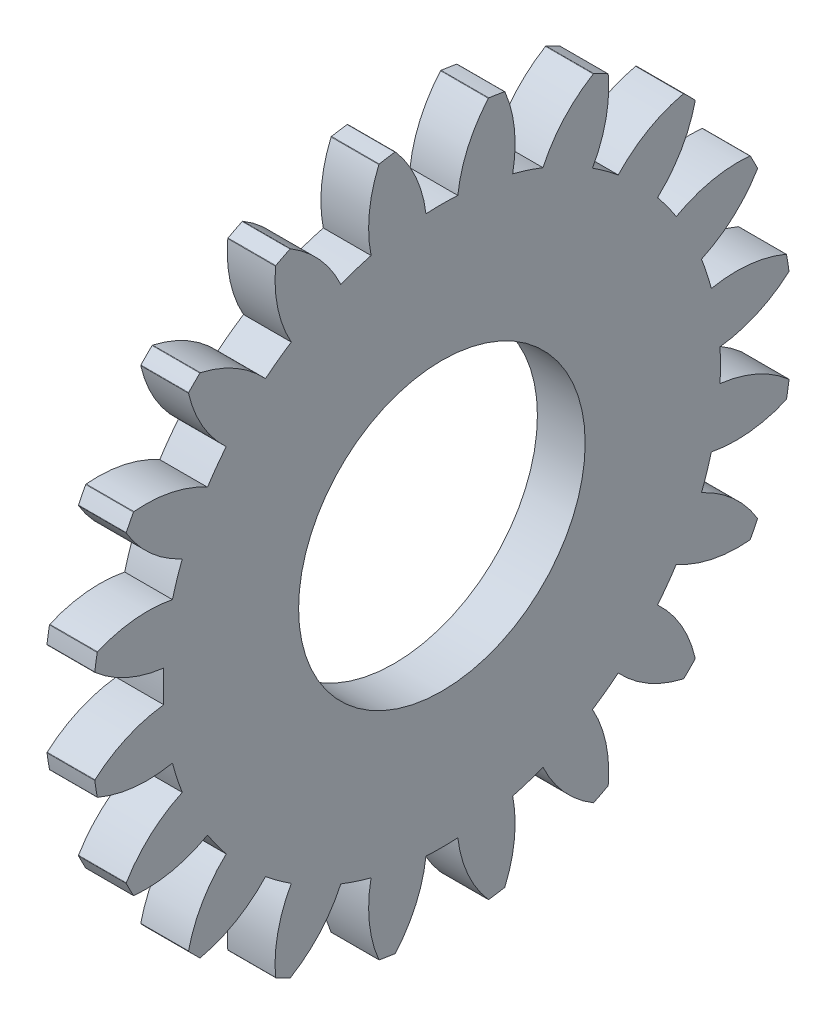
SolidWorks part; units mm, degrees
material "Zinc AC41A Alloy, As Cast"
ref_plane "Plane1" through (0, 0, 0) normal (0, 0, 1) x (1, 0, 0)
ref_plane "Plane2" through (0, 0, 0) normal (0, 1, 0) x (1, 0, 0)
ref_plane "Plane3" through (0, 0, 0) normal (1, 0, 0) x (0, 0, -1)
sketch "HoldingSke" plane through (0, 0, 0) normal (0, 1, 0) x (1, 0, 0)
  line L0 (0, 0) -> (0.9397, -0.342)
  line L1 (-15, 0) -> (100, 0) construction
  line L2 (0, 0) -> (-2.1039, 2.3779)
  line L3 (0, 0) -> (-11.863, 4.5341)
  line L4 (0, 0) -> (8.1152, 2.9537)
  line L5 (0, 0) -> (-46.8476, -17.4728)
  line L6 (0, 0) -> (-1.2434, -0.839)
  line L7 (-2.1039, 2.3779) -> (8.6586, 51.2059)
  line L8 (-76.2, 54.61) -> (-74.8, 54.61)
  line L9 (-71.009, 38.7566) -> (-53.1078, 45.2721)
  line L10 (-76.2, 71.12) -> (104.1128, 71.12)
  line L11 (0, 0) -> (-1.5, 0)
  line L12 (-76.2, 101.6) -> (-76.162, 101.6)
  line L13 (24.9733, 27.94) -> (52.9518, 28.4284)
  line L14 (24.9733, 27.94) -> (24.9743, 27.94)
  line L15 (24.9733, 27.94) -> (100.4006, 29.5858)
  line L16 (-63.627, -1) -> (-12.827, -1)
  circle A0 centre (0, 0) radius 4.5
  circle A1 centre (0, 0) radius 8.749
  circle A2 centre (0, 0) radius 37.5
  circle A3 centre (0, 0) radius 4.5
  dimension "MHD" = 17.498
  dimension "Hub_dia" = 75
  dimension "Bore" = 9
  dimension "MBD" = 9
  dimension "Num_teeth" = 20
  dimension "Pitch" = 1
  dimension "Overall_len" = 50
  dimension "Show_teeth" = 20
  dimension "Thickness" = 1.5
  dimension "OAL" = 50.0001
  dimension "T_dim" = 1.4
  dimension "Ap" = 20
  dimension "H" = 19.05
  dimension "Pitch_radius" = 180.3128
  dimension "Width" = 1.5
  dimension "Backlash" = 0.038
  dimension "Addendum_fac" = 1
  dimension "Dedendum_fac" = 1.25
  dimension "Clearance_fac" = 0.25
  dimension "Dedendum_add" = 0.001
  dimension "Module" = 1
sketch "BasProSke" plane through (0, 0, 0) normal (0, 1, 0) x (1, 0, 0)
  line L0 (-10, 0) -> (60, 0) construction
  line L1 (0, 0) -> (0, 11)
  line L2 (0, 0) -> (1.5, 0)
  line L3 (1.5, 0) -> (1.5, 11)
  line L4 (1.5, 11) -> (0, 11)
  dimension "Thickness" = 1.5
  dimension "Diameter" = 22
revolve "Base-Revolve" add sketch "BasProSke" angle 360 about L0
sketch "TooCutSke" plane through (0, 0, 0) normal (1, 0, 0) x (0, 0, -1)
  line L1 (0, 0) -> (0, 107) construction
  line L2 (0, 0) -> (-0.8511, 9.9637) construction
  line L3 (0, 0) -> (-3.1206, 19.7028) construction
  line L4 (-0.8511, 9.9637) -> (-1.5603, 9.8514) construction
  arc A0 (0.4999, 8.7347) -> (-0.4999, 8.7347) centre (0, 0) ccw
  arc A1 (1.4852, 10.9249) -> (-1.4852, 10.9249) centre (0, 0) ccw
  circle A2 centre (0, 0) radius 10 construction
  circle A3 centre (0, 0) radius 9.3969 construction
  arc A4 (-0.4999, 8.7347) -> (-1.4852, 10.9249) centre (-4.4722, 8.2645) ccw
  arc A5 (1.4852, 10.9249) -> (0.4999, 8.7347) centre (4.4722, 8.2645) ccw
  dimension "Root_dia" = 17.498
  dimension "Overcut_dia" = 22.0508
  dimension "Pitch_dia" = 20
  dimension "Base_dia" = 18.7939
  dimension "Flank_rad" = 4
  dimension "Half_ang" = 9
  dimension "Half_CT" = 0.7181
extrude "ToothCut" cut sketch "TooCutSke" along normal through all
fillet "Breaks" radius 0.02 2 edges at (0.75, 10.902, -1.465) (0.75, 10.902, 1.465)
fillet "RootFillets" [suppressed] radius 0.251
pattern_circular "TeethCuts" count 20 every 18 about axis through (-10, 0, 0) along (1, 0, 0) of "ToothCut", "RootFillets", "Breaks"
sketch "HubNeaOneSke" plane through (0, 0, 0) normal (-1, 0, 0) x (0, 0, 1)
  circle A0 centre (0, 0) radius 8.749
  dimension "Diameter" = 17.498
extrude "HubNearOne" [suppressed] add sketch "HubNeaOneSke" along normal blind 48.5001
sketch "HubNeaBotSke" plane through (0, 0, 0) normal (-1, 0, 0) x (0, 0, 1)
  circle A0 centre (0, 0) radius 8.749
  dimension "Diameter" = 17.498
extrude "HubNearBoth" [suppressed] add sketch "HubNeaBotSke" along normal blind 24.25
ref_plane "FarPln" through (1.5, 0, 0) normal (1, 0, 0) x (0, 0, -1)
sketch "HubFarSke" plane through (1.5, 0, 0) normal (1, 0, 0) x (0, 0, -1)
  circle A0 centre (0, 0) radius 8.749
  dimension "Diameter" = 17.498
extrude "HubFar" [suppressed] add sketch "HubFarSke" along normal blind 24.25
sketch "BorSke" plane through (0, 0, 0) normal (1, 0, 0) x (0, 0, -1)
  circle A0 centre (0, 0) radius 4.5
  dimension "Diameter" = 9
extrude "Bore" cut sketch "BorSke" along normal mid plane 100.0001
sketch "KeySke" plane through (0, 0, 0) normal (1, 0, 0) x (0, 0, -1)
  line L0 (-1.5, 0) -> (-1.5, 5.9)
  line L1 (-1.5, 5.9) -> (1.5, 5.9)
  line L2 (1.5, 5.9) -> (1.5, 0)
  line L3 (0, 0) -> (0, 34) construction
  line L4 (-1.5, 0) -> (1.5, 0)
  dimension "Offset" = 5.9
  dimension "Width" = 3
extrude "Keyway" [suppressed] cut sketch "KeySke" along normal mid plane 100.0001
pattern_circular "Keyway2" [suppressed] count 2 every 90 about axis through (-10, 0, 0) along (1, 0, 0)
equation "' \"Module@HoldingSke\" = 6.35"
equation "' \"Num_teeth@HoldingSke\" = 12"
equation "' \"Ap@HoldingSke\" =  20"
equation "' \"Ap@HoldingSke\" = 20"
equation "' \"Width@HoldingSke\" = 0.5 * 25.4"
equation "' \"Hub_dia@HoldingSke\"= 1 * 25.4"
equation "' \"Hub_dia@HoldingSke\" = 1 * 25.4"
equation "' \"Overall_len@HoldingSke\" = 1.0 * 25.4"
equation "' \"Bore@HoldingSke\" = 0.75 * 25.4"
equation "' \"T_dim@HoldingSke\" = 0.1 * 25.4"
equation "' \"Width@KeySke\" = 0.25 * 25.4"
equation "' \"Show_teeth@HoldingSke\" = 13"
equation "' \"Backlash@HoldingSke\" = 0.009 * 25.4"
equation "' \"Addendum_fac@HoldingSke\" = 1.0"
equation "' \"Dedendum_fac@HoldingSke\" = 1.25"
equation "' \"Dedendum_add@HoldingSke\" = 0.00005 * 25.4"
equation "' \"Clearance_fac@HoldingSke\" = 0.25"
equation "\"Pitch@HoldingSke\" = 1 / \"Module@HoldingSke\""
equation "\"Overcut_dia@TooCutSke\" = (\"Num_teeth@HoldingSke\" + 2 * \"Addendum_fac@HoldingSke\") / \"Pitch@HoldingSke\" + 0.002 * 25.4"
equation "\"Pitch_dia@TooCutSke\" = \"Num_teeth@HoldingSke\" / \"Pitch@HoldingSke\""
equation "\"Base_dia@TooCutSke\" = \"Num_teeth@HoldingSke\" / \"Pitch@HoldingSke\" * cos((\"Ap@HoldingSke\"  * 3.14159265 / 180))"
equation "\"Root_dia@TooCutSke\" = (\"Num_teeth@HoldingSke\" + 2) / \"Pitch@HoldingSke\" - 2 * (\"Addendum_fac@HoldingSke\" + \"Dedendum_fac@HoldingSke\") / \"Pitch@HoldingSke\" - \"Dedendum_add@HoldingSke\" * 2"
equation "\"Half_ang@TooCutSke\" = 180 / \"Num_teeth@HoldingSke\""
equation "\"Half_CT@TooCutSke\" = \"Num_teeth@HoldingSke\" / \"Pitch@HoldingSke\" * sin((3.14159265 / 2 / \"Num_teeth@HoldingSke\")) / 2 - 7 * \"Backlash@HoldingSke\" / 4"
equation "\"Flank_rad@TooCutSke\" = \"Num_teeth@HoldingSke\" / \"Pitch@HoldingSke\" / 5"
equation "\"Radius@RootFillets\" = \"Clearance_fac@HoldingSke\" / \"Pitch@HoldingSke\" + \"Dedendum_add@HoldingSke\""
equation "\"Break_rad@Breaks\" = 0.02 / \"Pitch@HoldingSke\""
equation "\"Thickness@HoldingSke\" = \"Width@HoldingSke\""
equation "\"OAL@HoldingSke\" = \"Thickness@HoldingSke\""
equation "\"MHD@HoldingSke\" = (\"Num_teeth@HoldingSke\" + 2) / \"Pitch@HoldingSke\" - 2 * (\"Addendum_fac@HoldingSke\" + \"Dedendum_fac@HoldingSke\")  / \"Pitch@HoldingSke\" - \"Dedendum_add@HoldingSke\" * 2"
equation "\"MBD@HoldingSke\" = (\"Num_teeth@HoldingSke\" + 2) / \"Pitch@HoldingSke\" - 2 * (\"Addendum_fac@HoldingSke\" + \"Dedendum_fac@HoldingSke\")  / \"Pitch@HoldingSke\" - \"Dedendum_add@HoldingSke\" * 2 - 0.002 * 25.4"
equation "\"MHD@HoldingSke\" = ((sgn( \"MHD@HoldingSke\" - \"Hub_dia@HoldingSke\" )-1)*( \"MHD@HoldingSke\" - \"Hub_dia@HoldingSke\" ))/-2+ \"Hub_dia@HoldingSke\""
equation "\"MBD@HoldingSke\" = ((sgn( \"MBD@HoldingSke\" - \"Bore@HoldingSke\" )-1)*( \"MBD@HoldingSke\" - \"Bore@HoldingSke\" ))/-2+ \"Bore@HoldingSke\""
equation "\"OAL@HoldingSke\" = ((sgn( \"OAL@HoldingSke\" - \"Overall_len@HoldingSke\" )+1)*( \"OAL@HoldingSke\" - \"Overall_len@HoldingSke\" ))/2 + \"Overall_len@HoldingSke\" + 0.000002 * 25.4"
equation "\"Num_teeth@TeethCuts\" = int( \"Show_teeth@HoldingSke\" ) + 1"
equation "\"Num_teeth@TeethCuts\" = ((sgn( \"Num_teeth@TeethCuts\" - \"Num_teeth@HoldingSke\" )-1)*( \"Num_teeth@TeethCuts\" - \"Num_teeth@HoldingSke\" ))/-2+ \"Num_teeth@HoldingSke\""
equation "\"Num_teeth@TeethCuts\" = ((sgn( \"Num_teeth@TeethCuts\" - 2.0)+1)*( \"Num_teeth@TeethCuts\" - 2.0))/2 +2.0"
equation "\"Angle@TeethCuts\" = 360.0 / \"Num_teeth@HoldingSke\""
equation "\"Diameter@BasProSke\" = (\"Num_teeth@HoldingSke\" + 2 * \"Addendum_fac@HoldingSke\") / \"Pitch@HoldingSke\""
equation "\"Thickness@BasProSke\"  = \"Thickness@HoldingSke\""
equation "' \"Fillet_rad@BasProSke\" =  \"Thickness@HoldingSke\" * 0.05"
equation "' \"Fillet_rad@BasProSke\" = \"Thickness@HoldingSke\" * 0.05"
equation "\"MHD@HoldingSke\" = ((sgn( \"MHD@HoldingSke\" - \"Root_dia@TooCutSke\" )-1)*( \"MHD@HoldingSke\" - \"Root_dia@TooCutSke\" ))/-2+ \"Root_dia@TooCutSke\""
equation "\"Diameter@HubNeaOneSke\" = \"MHD@HoldingSke\""
equation "\"Length@HubNearOne\" = \"OAL@HoldingSke\" - \"Thickness@BasProSke\""
equation "\"Diameter@HubNeaBotSke\" = \"MHD@HoldingSke\""
equation "\"Length@HubNearBoth\" = ( \"OAL@HoldingSke\" - \"Thickness@BasProSke\" ) / 2.0"
equation "\"Thickness@FarPln\" = \"Thickness@BasProSke\""
equation "\"Diameter@HubFarSke\" = \"MHD@HoldingSke\""
equation "\"Length@HubFar\" = ( \"OAL@HoldingSke\" - \"Thickness@BasProSke\" ) / 2.0"
equation "\"Diameter@BorSke\" = \"MBD@HoldingSke\""
equation "\"D1@Bore\" = \"OAL@HoldingSke\" * 2.0"
equation "\"D1@Keyway\" = \"OAL@HoldingSke\" * 2.0"
equation "\"Offset@KeySke\" = \"T_dim@HoldingSke\" + \"MBD@HoldingSke\" / 2.0"
